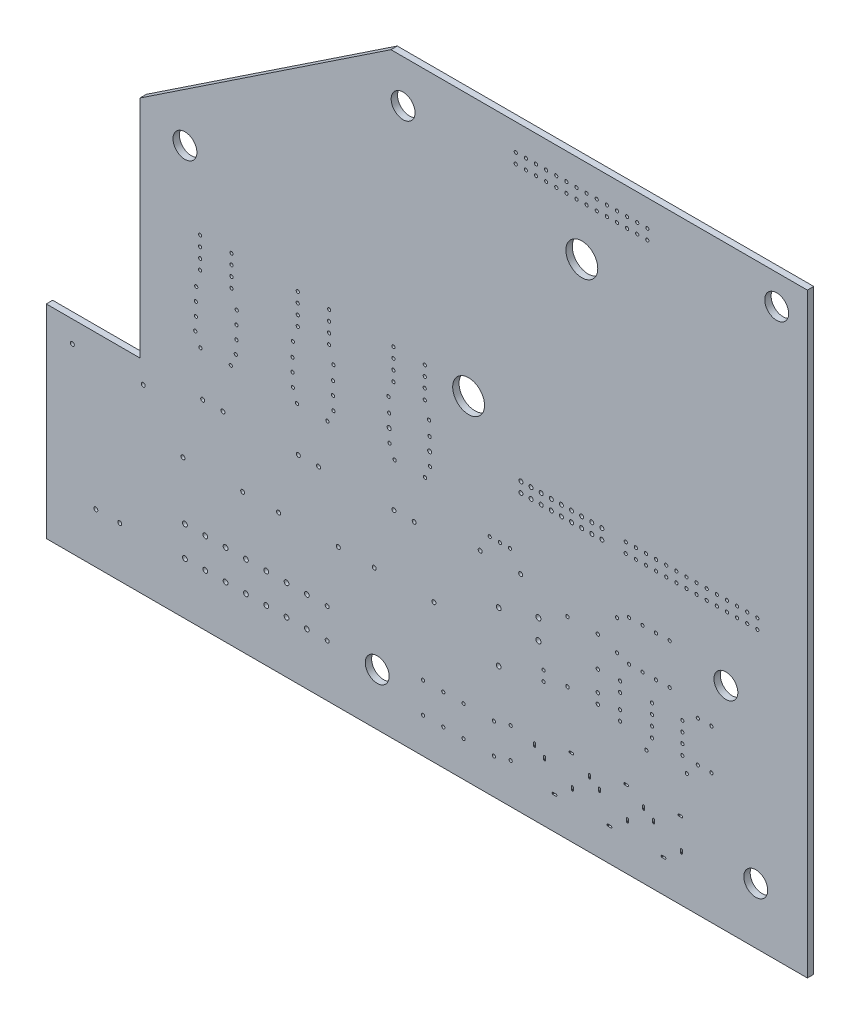
SolidWorks part; units mm, degrees
ref_plane "Front Plane" through (0, 0, 0) normal (0, 0, 1) x (1, 0, 0)
ref_plane "Top Plane" through (0, 0, 0) normal (0, 1, 0) x (1, 0, 0)
ref_plane "Right Plane" through (0, 0, 0) normal (1, 0, 0) x (0, 0, -1)
ref_plane "Plane1" through (0, 0, 0) normal (0, 0, -1) x (-1, 0, 0)
sketch "Sketch1" plane through (0, 0, 0) normal (0, 0, -1) x (-1, 0, 0)
  line L0 (-318, -203.5) -> (-127, -203.5)
  line L1 (-127, -203.5) -> (-127, -152.5)
  line L2 (-127, -152.5) -> (-150.5, -152.5)
  line L3 (-150.5, -152.5) -> (-150.5, -96)
  line L4 (-150.5, -96) -> (-213.5, -54)
  line L5 (-213.5, -54) -> (-318, -54)
  line L6 (-318, -54) -> (-318, -203.5)
  line L7 (-286.2232, -191.2732) -> (-286.169, -191.3543)
  line L8 (-286.169, -191.3543) -> (-286.15, -191.45)
  line L9 (-286.15, -191.45) -> (-286.15, -192.15)
  line L10 (-286.15, -192.15) -> (-286.169, -192.2457)
  line L11 (-286.169, -192.2457) -> (-286.2232, -192.3268)
  line L12 (-286.2232, -192.3268) -> (-286.3043, -192.381)
  line L13 (-286.3043, -192.381) -> (-286.4, -192.4)
  line L14 (-286.4, -192.4) -> (-286.4957, -192.381)
  line L15 (-286.4957, -192.381) -> (-286.5768, -192.3268)
  line L16 (-286.5768, -192.3268) -> (-286.631, -192.2457)
  line L17 (-286.631, -192.2457) -> (-286.65, -192.15)
  line L18 (-286.65, -192.15) -> (-286.65, -191.45)
  line L19 (-286.65, -191.45) -> (-286.631, -191.3543)
  line L20 (-286.631, -191.3543) -> (-286.5768, -191.2732)
  line L21 (-286.5768, -191.2732) -> (-286.4957, -191.219)
  line L22 (-286.4957, -191.219) -> (-286.4, -191.2)
  line L23 (-286.4, -191.2) -> (-286.3043, -191.219)
  line L24 (-286.3043, -191.219) -> (-286.2232, -191.2732)
  line L25 (-282.4268, -195.1232) -> (-282.3457, -195.069)
  line L26 (-282.3457, -195.069) -> (-282.25, -195.05)
  line L27 (-282.25, -195.05) -> (-281.55, -195.05)
  line L28 (-281.55, -195.05) -> (-281.4543, -195.069)
  line L29 (-281.4543, -195.069) -> (-281.3732, -195.1232)
  line L30 (-281.3732, -195.1232) -> (-281.319, -195.2043)
  line L31 (-281.319, -195.2043) -> (-281.3, -195.3)
  line L32 (-281.3, -195.3) -> (-281.319, -195.3957)
  line L33 (-281.319, -195.3957) -> (-281.3732, -195.4768)
  line L34 (-281.3732, -195.4768) -> (-281.4543, -195.531)
  line L35 (-281.4543, -195.531) -> (-281.55, -195.55)
  line L36 (-281.55, -195.55) -> (-282.25, -195.55)
  line L37 (-282.25, -195.55) -> (-282.3457, -195.531)
  line L38 (-282.3457, -195.531) -> (-282.4268, -195.4768)
  line L39 (-282.4268, -195.4768) -> (-282.481, -195.3957)
  line L40 (-282.481, -195.3957) -> (-282.5, -195.3)
  line L41 (-282.5, -195.3) -> (-282.481, -195.2043)
  line L42 (-282.481, -195.2043) -> (-282.4268, -195.1232)
  line L43 (-268.8718, -195.1232) -> (-268.7907, -195.069)
  line L44 (-268.7907, -195.069) -> (-268.695, -195.05)
  line L45 (-268.695, -195.05) -> (-267.995, -195.05)
  line L46 (-267.995, -195.05) -> (-267.8993, -195.069)
  line L47 (-267.8993, -195.069) -> (-267.8182, -195.1232)
  line L48 (-267.8182, -195.1232) -> (-267.764, -195.2043)
  line L49 (-267.764, -195.2043) -> (-267.745, -195.3)
  line L50 (-267.745, -195.3) -> (-267.764, -195.3957)
  line L51 (-267.764, -195.3957) -> (-267.8182, -195.4768)
  line L52 (-267.8182, -195.4768) -> (-267.8993, -195.531)
  line L53 (-267.8993, -195.531) -> (-267.995, -195.55)
  line L54 (-267.995, -195.55) -> (-268.695, -195.55)
  line L55 (-268.695, -195.55) -> (-268.7907, -195.531)
  line L56 (-268.7907, -195.531) -> (-268.8718, -195.4768)
  line L57 (-268.8718, -195.4768) -> (-268.926, -195.3957)
  line L58 (-268.926, -195.3957) -> (-268.945, -195.3)
  line L59 (-268.945, -195.3) -> (-268.926, -195.2043)
  line L60 (-268.926, -195.2043) -> (-268.8718, -195.1232)
  line L61 (-272.6682, -191.2732) -> (-272.614, -191.3543)
  line L62 (-272.614, -191.3543) -> (-272.595, -191.45)
  line L63 (-272.595, -191.45) -> (-272.595, -192.15)
  line L64 (-272.595, -192.15) -> (-272.614, -192.2457)
  line L65 (-272.614, -192.2457) -> (-272.6682, -192.3268)
  line L66 (-272.6682, -192.3268) -> (-272.7493, -192.381)
  line L67 (-272.7493, -192.381) -> (-272.845, -192.4)
  line L68 (-272.845, -192.4) -> (-272.9407, -192.381)
  line L69 (-272.9407, -192.381) -> (-273.0218, -192.3268)
  line L70 (-273.0218, -192.3268) -> (-273.076, -192.2457)
  line L71 (-273.076, -192.2457) -> (-273.095, -192.15)
  line L72 (-273.095, -192.15) -> (-273.095, -191.45)
  line L73 (-273.095, -191.45) -> (-273.076, -191.3543)
  line L74 (-273.076, -191.3543) -> (-273.0218, -191.2732)
  line L75 (-273.0218, -191.2732) -> (-272.9407, -191.219)
  line L76 (-272.9407, -191.219) -> (-272.845, -191.2)
  line L77 (-272.845, -191.2) -> (-272.7493, -191.219)
  line L78 (-272.7493, -191.219) -> (-272.6682, -191.2732)
  line L79 (-279.2232, -188.1732) -> (-279.169, -188.2543)
  line L80 (-279.169, -188.2543) -> (-279.15, -188.35)
  line L81 (-279.15, -188.35) -> (-279.15, -189.05)
  line L82 (-279.15, -189.05) -> (-279.169, -189.1457)
  line L83 (-279.169, -189.1457) -> (-279.2232, -189.2268)
  line L84 (-279.2232, -189.2268) -> (-279.3043, -189.281)
  line L85 (-279.3043, -189.281) -> (-279.4, -189.3)
  line L86 (-279.4, -189.3) -> (-279.4957, -189.281)
  line L87 (-279.4957, -189.281) -> (-279.5768, -189.2268)
  line L88 (-279.5768, -189.2268) -> (-279.631, -189.1457)
  line L89 (-279.631, -189.1457) -> (-279.65, -189.05)
  line L90 (-279.65, -189.05) -> (-279.65, -188.35)
  line L91 (-279.65, -188.35) -> (-279.631, -188.2543)
  line L92 (-279.631, -188.2543) -> (-279.5768, -188.1732)
  line L93 (-279.5768, -188.1732) -> (-279.4957, -188.119)
  line L94 (-279.4957, -188.119) -> (-279.4, -188.1)
  line L95 (-279.4, -188.1) -> (-279.3043, -188.119)
  line L96 (-279.3043, -188.119) -> (-279.2232, -188.1732)
  line L97 (-276.7232, -186.4732) -> (-276.669, -186.5543)
  line L98 (-276.669, -186.5543) -> (-276.65, -186.65)
  line L99 (-276.65, -186.65) -> (-276.65, -187.35)
  line L100 (-276.65, -187.35) -> (-276.669, -187.4457)
  line L101 (-276.669, -187.4457) -> (-276.7232, -187.5268)
  line L102 (-276.7232, -187.5268) -> (-276.8043, -187.581)
  line L103 (-276.8043, -187.581) -> (-276.9, -187.6)
  line L104 (-276.9, -187.6) -> (-276.9957, -187.581)
  line L105 (-276.9957, -187.581) -> (-277.0768, -187.5268)
  line L106 (-277.0768, -187.5268) -> (-277.131, -187.4457)
  line L107 (-277.131, -187.4457) -> (-277.15, -187.35)
  line L108 (-277.15, -187.35) -> (-277.15, -186.65)
  line L109 (-277.15, -186.65) -> (-277.131, -186.5543)
  line L110 (-277.131, -186.5543) -> (-277.0768, -186.4732)
  line L111 (-277.0768, -186.4732) -> (-276.9957, -186.419)
  line L112 (-276.9957, -186.419) -> (-276.9, -186.4)
  line L113 (-276.9, -186.4) -> (-276.8043, -186.419)
  line L114 (-276.8043, -186.419) -> (-276.7232, -186.4732)
  line L115 (-286.6268, -184.0232) -> (-286.5457, -183.969)
  line L116 (-286.5457, -183.969) -> (-286.45, -183.95)
  line L117 (-286.45, -183.95) -> (-285.75, -183.95)
  line L118 (-285.75, -183.95) -> (-285.6543, -183.969)
  line L119 (-285.6543, -183.969) -> (-285.5732, -184.0232)
  line L120 (-285.5732, -184.0232) -> (-285.519, -184.1043)
  line L121 (-285.519, -184.1043) -> (-285.5, -184.2)
  line L122 (-285.5, -184.2) -> (-285.519, -184.2957)
  line L123 (-285.519, -184.2957) -> (-285.5732, -184.3768)
  line L124 (-285.5732, -184.3768) -> (-285.6543, -184.431)
  line L125 (-285.6543, -184.431) -> (-285.75, -184.45)
  line L126 (-285.75, -184.45) -> (-286.45, -184.45)
  line L127 (-286.45, -184.45) -> (-286.5457, -184.431)
  line L128 (-286.5457, -184.431) -> (-286.6268, -184.3768)
  line L129 (-286.6268, -184.3768) -> (-286.681, -184.2957)
  line L130 (-286.681, -184.2957) -> (-286.7, -184.2)
  line L131 (-286.7, -184.2) -> (-286.681, -184.1043)
  line L132 (-286.681, -184.1043) -> (-286.6268, -184.0232)
  line L133 (-273.0718, -184.0232) -> (-272.9907, -183.969)
  line L134 (-272.9907, -183.969) -> (-272.895, -183.95)
  line L135 (-272.895, -183.95) -> (-272.195, -183.95)
  line L136 (-272.195, -183.95) -> (-272.0993, -183.969)
  line L137 (-272.0993, -183.969) -> (-272.0182, -184.0232)
  line L138 (-272.0182, -184.0232) -> (-271.964, -184.1043)
  line L139 (-271.964, -184.1043) -> (-271.945, -184.2)
  line L140 (-271.945, -184.2) -> (-271.964, -184.2957)
  line L141 (-271.964, -184.2957) -> (-272.0182, -184.3768)
  line L142 (-272.0182, -184.3768) -> (-272.0993, -184.431)
  line L143 (-272.0993, -184.431) -> (-272.195, -184.45)
  line L144 (-272.195, -184.45) -> (-272.895, -184.45)
  line L145 (-272.895, -184.45) -> (-272.9907, -184.431)
  line L146 (-272.9907, -184.431) -> (-273.0718, -184.3768)
  line L147 (-273.0718, -184.3768) -> (-273.126, -184.2957)
  line L148 (-273.126, -184.2957) -> (-273.145, -184.2)
  line L149 (-273.145, -184.2) -> (-273.126, -184.1043)
  line L150 (-273.126, -184.1043) -> (-273.0718, -184.0232)
  line L151 (-258.8682, -191.2732) -> (-258.814, -191.3543)
  line L152 (-258.814, -191.3543) -> (-258.795, -191.45)
  line L153 (-258.795, -191.45) -> (-258.795, -192.15)
  line L154 (-258.795, -192.15) -> (-258.814, -192.2457)
  line L155 (-258.814, -192.2457) -> (-258.8682, -192.3268)
  line L156 (-258.8682, -192.3268) -> (-258.9493, -192.381)
  line L157 (-258.9493, -192.381) -> (-259.045, -192.4)
  line L158 (-259.045, -192.4) -> (-259.1407, -192.381)
  line L159 (-259.1407, -192.381) -> (-259.2218, -192.3268)
  line L160 (-259.2218, -192.3268) -> (-259.276, -192.2457)
  line L161 (-259.276, -192.2457) -> (-259.295, -192.15)
  line L162 (-259.295, -192.15) -> (-259.295, -191.45)
  line L163 (-259.295, -191.45) -> (-259.276, -191.3543)
  line L164 (-259.276, -191.3543) -> (-259.2218, -191.2732)
  line L165 (-259.2218, -191.2732) -> (-259.1407, -191.219)
  line L166 (-259.1407, -191.219) -> (-259.045, -191.2)
  line L167 (-259.045, -191.2) -> (-258.9493, -191.219)
  line L168 (-258.9493, -191.219) -> (-258.8682, -191.2732)
  line L169 (-265.6682, -188.1732) -> (-265.614, -188.2543)
  line L170 (-265.614, -188.2543) -> (-265.595, -188.35)
  line L171 (-265.595, -188.35) -> (-265.595, -189.05)
  line L172 (-265.595, -189.05) -> (-265.614, -189.1457)
  line L173 (-265.614, -189.1457) -> (-265.6682, -189.2268)
  line L174 (-265.6682, -189.2268) -> (-265.7493, -189.281)
  line L175 (-265.7493, -189.281) -> (-265.845, -189.3)
  line L176 (-265.845, -189.3) -> (-265.9407, -189.281)
  line L177 (-265.9407, -189.281) -> (-266.0218, -189.2268)
  line L178 (-266.0218, -189.2268) -> (-266.076, -189.1457)
  line L179 (-266.076, -189.1457) -> (-266.095, -189.05)
  line L180 (-266.095, -189.05) -> (-266.095, -188.35)
  line L181 (-266.095, -188.35) -> (-266.076, -188.2543)
  line L182 (-266.076, -188.2543) -> (-266.0218, -188.1732)
  line L183 (-266.0218, -188.1732) -> (-265.9407, -188.119)
  line L184 (-265.9407, -188.119) -> (-265.845, -188.1)
  line L185 (-265.845, -188.1) -> (-265.7493, -188.119)
  line L186 (-265.7493, -188.119) -> (-265.6682, -188.1732)
  line L187 (-263.1682, -186.4732) -> (-263.114, -186.5543)
  line L188 (-263.114, -186.5543) -> (-263.095, -186.65)
  line L189 (-263.095, -186.65) -> (-263.095, -187.35)
  line L190 (-263.095, -187.35) -> (-263.114, -187.4457)
  line L191 (-263.114, -187.4457) -> (-263.1682, -187.5268)
  line L192 (-263.1682, -187.5268) -> (-263.2493, -187.581)
  line L193 (-263.2493, -187.581) -> (-263.345, -187.6)
  line L194 (-263.345, -187.6) -> (-263.4407, -187.581)
  line L195 (-263.4407, -187.581) -> (-263.5218, -187.5268)
  line L196 (-263.5218, -187.5268) -> (-263.576, -187.4457)
  line L197 (-263.576, -187.4457) -> (-263.595, -187.35)
  line L198 (-263.595, -187.35) -> (-263.595, -186.65)
  line L199 (-263.595, -186.65) -> (-263.576, -186.5543)
  line L200 (-263.576, -186.5543) -> (-263.5218, -186.4732)
  line L201 (-263.5218, -186.4732) -> (-263.4407, -186.419)
  line L202 (-263.4407, -186.419) -> (-263.345, -186.4)
  line L203 (-263.345, -186.4) -> (-263.2493, -186.419)
  line L204 (-263.2493, -186.419) -> (-263.1682, -186.4732)
  line L205 (-255.0718, -195.1232) -> (-254.9907, -195.069)
  line L206 (-254.9907, -195.069) -> (-254.895, -195.05)
  line L207 (-254.895, -195.05) -> (-254.195, -195.05)
  line L208 (-254.195, -195.05) -> (-254.0993, -195.069)
  line L209 (-254.0993, -195.069) -> (-254.0182, -195.1232)
  line L210 (-254.0182, -195.1232) -> (-253.964, -195.2043)
  line L211 (-253.964, -195.2043) -> (-253.945, -195.3)
  line L212 (-253.945, -195.3) -> (-253.964, -195.3957)
  line L213 (-253.964, -195.3957) -> (-254.0182, -195.4768)
  line L214 (-254.0182, -195.4768) -> (-254.0993, -195.531)
  line L215 (-254.0993, -195.531) -> (-254.195, -195.55)
  line L216 (-254.195, -195.55) -> (-254.895, -195.55)
  line L217 (-254.895, -195.55) -> (-254.9907, -195.531)
  line L218 (-254.9907, -195.531) -> (-255.0718, -195.4768)
  line L219 (-255.0718, -195.4768) -> (-255.126, -195.3957)
  line L220 (-255.126, -195.3957) -> (-255.145, -195.3)
  line L221 (-255.145, -195.3) -> (-255.126, -195.2043)
  line L222 (-255.126, -195.2043) -> (-255.0718, -195.1232)
  line L223 (-251.8682, -188.1732) -> (-251.814, -188.2543)
  line L224 (-251.814, -188.2543) -> (-251.795, -188.35)
  line L225 (-251.795, -188.35) -> (-251.795, -189.05)
  line L226 (-251.795, -189.05) -> (-251.814, -189.1457)
  line L227 (-251.814, -189.1457) -> (-251.8682, -189.2268)
  line L228 (-251.8682, -189.2268) -> (-251.9493, -189.281)
  line L229 (-251.9493, -189.281) -> (-252.045, -189.3)
  line L230 (-252.045, -189.3) -> (-252.1407, -189.281)
  line L231 (-252.1407, -189.281) -> (-252.2218, -189.2268)
  line L232 (-252.2218, -189.2268) -> (-252.276, -189.1457)
  line L233 (-252.276, -189.1457) -> (-252.295, -189.05)
  line L234 (-252.295, -189.05) -> (-252.295, -188.35)
  line L235 (-252.295, -188.35) -> (-252.276, -188.2543)
  line L236 (-252.276, -188.2543) -> (-252.2218, -188.1732)
  line L237 (-252.2218, -188.1732) -> (-252.1407, -188.119)
  line L238 (-252.1407, -188.119) -> (-252.045, -188.1)
  line L239 (-252.045, -188.1) -> (-251.9493, -188.119)
  line L240 (-251.9493, -188.119) -> (-251.8682, -188.1732)
  line L241 (-249.3682, -186.4732) -> (-249.314, -186.5543)
  line L242 (-249.314, -186.5543) -> (-249.295, -186.65)
  line L243 (-249.295, -186.65) -> (-249.295, -187.35)
  line L244 (-249.295, -187.35) -> (-249.314, -187.4457)
  line L245 (-249.314, -187.4457) -> (-249.3682, -187.5268)
  line L246 (-249.3682, -187.5268) -> (-249.4493, -187.581)
  line L247 (-249.4493, -187.581) -> (-249.545, -187.6)
  line L248 (-249.545, -187.6) -> (-249.6407, -187.581)
  line L249 (-249.6407, -187.581) -> (-249.7218, -187.5268)
  line L250 (-249.7218, -187.5268) -> (-249.776, -187.4457)
  line L251 (-249.776, -187.4457) -> (-249.795, -187.35)
  line L252 (-249.795, -187.35) -> (-249.795, -186.65)
  line L253 (-249.795, -186.65) -> (-249.776, -186.5543)
  line L254 (-249.776, -186.5543) -> (-249.7218, -186.4732)
  line L255 (-249.7218, -186.4732) -> (-249.6407, -186.419)
  line L256 (-249.6407, -186.419) -> (-249.545, -186.4)
  line L257 (-249.545, -186.4) -> (-249.4493, -186.419)
  line L258 (-249.4493, -186.419) -> (-249.3682, -186.4732)
  line L259 (-259.2718, -184.0232) -> (-259.1907, -183.969)
  line L260 (-259.1907, -183.969) -> (-259.095, -183.95)
  line L261 (-259.095, -183.95) -> (-258.395, -183.95)
  line L262 (-258.395, -183.95) -> (-258.2993, -183.969)
  line L263 (-258.2993, -183.969) -> (-258.2182, -184.0232)
  line L264 (-258.2182, -184.0232) -> (-258.164, -184.1043)
  line L265 (-258.164, -184.1043) -> (-258.145, -184.2)
  line L266 (-258.145, -184.2) -> (-258.164, -184.2957)
  line L267 (-258.164, -184.2957) -> (-258.2182, -184.3768)
  line L268 (-258.2182, -184.3768) -> (-258.2993, -184.431)
  line L269 (-258.2993, -184.431) -> (-258.395, -184.45)
  line L270 (-258.395, -184.45) -> (-259.095, -184.45)
  line L271 (-259.095, -184.45) -> (-259.1907, -184.431)
  line L272 (-259.1907, -184.431) -> (-259.2718, -184.3768)
  line L273 (-259.2718, -184.3768) -> (-259.326, -184.2957)
  line L274 (-259.326, -184.2957) -> (-259.345, -184.2)
  line L275 (-259.345, -184.2) -> (-259.326, -184.1043)
  line L276 (-259.326, -184.1043) -> (-259.2718, -184.0232)
  circle A0 centre (-305.05, -189.44) radius 3
  circle A1 centre (-293.91, -170.95) radius 0.4
  circle A2 centre (-287.755, -174.19) radius 0.4
  circle A3 centre (-290.51, -170.95) radius 0.4
  circle A4 centre (-286.625, -170.81) radius 0.4
  circle A5 centre (-277.595, -174.19) radius 0.4
  circle A6 centre (-279.005, -170.81) radius 0.4
  circle A7 centre (-271.005, -171.19) radius 0.4
  circle A8 centre (-286.625, -168.27) radius 0.4
  circle A9 centre (-286.625, -165.73) radius 0.4
  circle A10 centre (-286.625, -163.19) radius 0.4
  circle A11 centre (-279.005, -168.27) radius 0.4
  circle A12 centre (-279.005, -165.73) radius 0.4
  circle A13 centre (-271.005, -168.69) radius 0.4
  circle A14 centre (-279.005, -163.19) radius 0.4
  circle A15 centre (-271.005, -164.94) radius 0.4
  circle A16 centre (-271.005, -162.44) radius 0.4
  circle A17 centre (-243.55, -193.44) radius 0.4
  circle A18 centre (-239.34, -194.62) radius 0.4
  circle A19 centre (-239.34, -187) radius 0.4
  circle A20 centre (-231.72, -194.62) radius 0.4
  circle A21 centre (-226.64, -194.62) radius 0.4
  circle A22 centre (-231.72, -187) radius 0.4
  circle A23 centre (-226.64, -187) radius 0.4
  circle A24 centre (-243.55, -185.82) radius 0.4
  circle A25 centre (-265.42, -170.31) radius 0.425
  circle A26 centre (-257.8, -170.31) radius 0.425
  circle A27 centre (-251.8, -172.19) radius 0.4
  circle A28 centre (-265.42, -167.77) radius 0.425
  circle A29 centre (-265.42, -162.69) radius 0.425
  circle A30 centre (-251.8, -169.69) radius 0.4
  circle A31 centre (-250.5, -163.94) radius 0.65
  circle A32 centre (-240.55, -174.44) radius 0.6
  circle A33 centre (-240.55, -161.74) radius 0.6
  circle A34 centre (-224.293, -168.683) radius 0.5
  circle A35 centre (-293.91, -160.79) radius 0.4
  circle A36 centre (-297.55, -150.19) radius 3
  circle A37 centre (-290.51, -160.79) radius 0.4
  circle A38 centre (-283.45, -157.635) radius 0.4
  circle A39 centre (-280.005, -157.69) radius 0.4
  circle A40 centre (-276.64, -157.69) radius 0.4
  circle A41 centre (-273.255, -157.69) radius 0.4
  circle A42 centre (-270.255, -156.69) radius 0.4
  circle A43 centre (-283.45, -147.475) radius 0.4
  circle A44 centre (-280.005, -147.53) radius 0.4
  circle A45 centre (-270.255, -149.07) radius 0.4
  circle A46 centre (-276.64, -147.53) radius 0.4
  circle A47 centre (-273.255, -147.53) radius 0.4
  circle A48 centre (-305.44, -134.04) radius 0.4
  circle A49 centre (-302.9, -134.04) radius 0.4
  circle A50 centre (-305.44, -131.5) radius 0.4
  circle A51 centre (-302.9, -131.5) radius 0.4
  circle A52 centre (-300.36, -134.04) radius 0.4
  circle A53 centre (-297.82, -134.04) radius 0.4
  circle A54 centre (-300.36, -131.5) radius 0.4
  circle A55 centre (-297.82, -131.5) radius 0.4
  circle A56 centre (-295.28, -134.04) radius 0.4
  circle A57 centre (-292.74, -134.04) radius 0.4
  circle A58 centre (-295.28, -131.5) radius 0.4
  circle A59 centre (-292.74, -131.5) radius 0.4
  circle A60 centre (-290.2, -134.04) radius 0.4
  circle A61 centre (-287.66, -134.04) radius 0.4
  circle A62 centre (-290.2, -131.5) radius 0.4
  circle A63 centre (-287.66, -131.5) radius 0.4
  circle A64 centre (-285.12, -134.04) radius 0.4
  circle A65 centre (-282.58, -134.04) radius 0.4
  circle A66 centre (-280.04, -134.04) radius 0.4
  circle A67 centre (-285.12, -131.5) radius 0.4
  circle A68 centre (-282.58, -131.5) radius 0.4
  circle A69 centre (-280.04, -131.5) radius 0.4
  circle A70 centre (-277.5, -134.04) radius 0.4
  circle A71 centre (-274.96, -134.04) radius 0.4
  circle A72 centre (-277.5, -131.5) radius 0.4
  circle A73 centre (-274.96, -131.5) radius 0.4
  circle A74 centre (-272.42, -134.04) radius 0.4
  circle A75 centre (-272.42, -131.5) radius 0.4
  circle A76 centre (-265.42, -155.07) radius 0.425
  circle A77 centre (-257.8, -155.07) radius 0.425
  circle A78 centre (-250.5, -158.94) radius 0.65
  circle A79 centre (-246.05, -151.69) radius 0.5
  circle A80 centre (-235.89, -151.69) radius 0.5
  circle A81 centre (-243.38, -147.44) radius 0.4
  circle A82 centre (-240.84, -147.44) radius 0.4
  circle A83 centre (-238.3, -147.44) radius 0.4
  circle A84 centre (-266.44, -134.04) radius 0.5
  circle A85 centre (-263.9, -134.04) radius 0.5
  circle A86 centre (-266.44, -131.5) radius 0.5
  circle A87 centre (-263.9, -131.5) radius 0.5
  circle A88 centre (-261.36, -134.04) radius 0.5
  circle A89 centre (-258.82, -134.04) radius 0.5
  circle A90 centre (-261.36, -131.5) radius 0.5
  circle A91 centre (-258.82, -131.5) radius 0.5
  circle A92 centre (-256.28, -134.04) radius 0.5
  circle A93 centre (-253.74, -134.04) radius 0.5
  circle A94 centre (-256.28, -131.5) radius 0.5
  circle A95 centre (-253.74, -131.5) radius 0.5
  circle A96 centre (-251.2, -134.04) radius 0.5
  circle A97 centre (-248.66, -134.04) radius 0.5
  circle A98 centre (-246.12, -134.04) radius 0.5
  circle A99 centre (-251.2, -131.5) radius 0.5
  circle A100 centre (-248.66, -131.5) radius 0.5
  circle A101 centre (-246.12, -131.5) radius 0.5
  circle A102 centre (-223.3, -139.69) radius 0.4
  circle A103 centre (-223.21, -136.44) radius 0.5
  circle A104 centre (-223.21, -133.19) radius 0.4
  circle A105 centre (-221.56, -194.62) radius 0.4
  circle A106 centre (-221.56, -187) radius 0.4
  circle A107 centre (-210.05, -190.44) radius 3
  circle A108 centre (-197.5, -190.44) radius 0.5
  circle A109 centre (-192.4, -190.44) radius 0.6
  circle A110 centre (-187.3, -190.44) radius 0.6
  circle A111 centre (-182.2, -190.44) radius 0.6
  circle A112 centre (-197.5, -182.94) radius 0.5
  circle A113 centre (-192.4, -182.94) radius 0.6
  circle A114 centre (-187.3, -182.94) radius 0.6
  circle A115 centre (-182.2, -182.94) radius 0.6
  circle A116 centre (-209.307, -168.683) radius 0.5
  circle A117 centre (-200.293, -168.683) radius 0.5
  circle A118 centre (-185.307, -168.683) radius 0.5
  circle A119 centre (-177.1, -190.44) radius 0.6
  circle A120 centre (-172, -190.44) radius 0.6
  circle A121 centre (-166.9, -190.44) radius 0.6
  circle A122 centre (-161.8, -190.44) radius 0.6
  circle A123 centre (-177.1, -182.94) radius 0.6
  circle A124 centre (-172, -182.94) radius 0.6
  circle A125 centre (-166.9, -182.94) radius 0.6
  circle A126 centre (-161.8, -182.94) radius 0.6
  circle A127 centre (-145.44, -190.91) radius 0.5
  circle A128 centre (-139.44, -190.91) radius 0.5
  circle A129 centre (-176.293, -168.683) radius 0.5
  circle A130 centre (-161.307, -168.683) radius 0.5
  circle A131 centre (-219.34, -153.697) radius 0.5
  circle A132 centre (-214.26, -153.697) radius 0.5
  circle A133 centre (-195.34, -153.697) radius 0.5
  circle A134 centre (-190.26, -153.697) radius 0.5
  circle A135 centre (-222.05, -142.69) radius 0.4
  circle A136 centre (-214.43, -142.69) radius 0.4
  circle A137 centre (-213.14, -139.69) radius 0.4
  circle A138 centre (-213.05, -136.44) radius 0.5
  circle A139 centre (-213.05, -133.19) radius 0.4
  circle A140 centre (-223.05, -129.69) radius 0.4
  circle A141 centre (-212.89, -129.69) radius 0.4
  circle A142 centre (-197.55, -142.69) radius 0.4
  circle A143 centre (-189.93, -142.69) radius 0.4
  circle A144 centre (-199.05, -139.69) radius 0.4
  circle A145 centre (-198.96, -136.44) radius 0.4
  circle A146 centre (-188.89, -139.69) radius 0.4
  circle A147 centre (-188.8, -136.44) radius 0.4
  circle A148 centre (-198.96, -133.19) radius 0.4
  circle A149 centre (-199.05, -129.69) radius 0.4
  circle A150 centre (-188.8, -133.19) radius 0.4
  circle A151 centre (-188.89, -129.69) radius 0.4
  circle A152 centre (-171.34, -153.697) radius 0.5
  circle A153 centre (-166.26, -153.697) radius 0.5
  circle A154 centre (-151.34, -157.91) radius 0.5
  circle A155 centre (-133.54, -157.91) radius 0.5
  circle A156 centre (-173.3, -142.69) radius 0.4
  circle A157 centre (-174.55, -139.69) radius 0.4
  circle A158 centre (-174.71, -136.44) radius 0.4
  circle A159 centre (-165.68, -142.69) radius 0.4
  circle A160 centre (-164.39, -139.69) radius 0.4
  circle A161 centre (-164.55, -136.44) radius 0.4
  circle A162 centre (-174.71, -133.19) radius 0.4
  circle A163 centre (-174.8, -129.94) radius 0.4
  circle A164 centre (-164.55, -133.19) radius 0.4
  circle A165 centre (-164.64, -129.94) radius 0.4
  circle A166 centre (-232.99, -119.55) radius 4
  circle A167 centre (-310.3, -61.44) radius 3
  circle A168 centre (-277.84, -63.2) radius 0.4
  circle A169 centre (-275.3, -63.2) radius 0.4
  circle A170 centre (-272.76, -63.2) radius 0.4
  circle A171 centre (-270.22, -63.2) radius 0.4
  circle A172 centre (-277.84, -60.66) radius 0.4
  circle A173 centre (-275.3, -60.66) radius 0.4
  circle A174 centre (-272.76, -60.66) radius 0.4
  circle A175 centre (-270.22, -60.66) radius 0.4
  circle A176 centre (-261.4, -75.61) radius 4
  circle A177 centre (-267.68, -63.2) radius 0.4
  circle A178 centre (-265.14, -63.2) radius 0.4
  circle A179 centre (-262.6, -63.2) radius 0.4
  circle A180 centre (-260.06, -63.2) radius 0.4
  circle A181 centre (-257.52, -63.2) radius 0.4
  circle A182 centre (-267.68, -60.66) radius 0.4
  circle A183 centre (-265.14, -60.66) radius 0.4
  circle A184 centre (-262.6, -60.66) radius 0.4
  circle A185 centre (-260.06, -60.66) radius 0.4
  circle A186 centre (-257.52, -60.66) radius 0.4
  circle A187 centre (-254.98, -63.2) radius 0.4
  circle A188 centre (-252.44, -63.2) radius 0.4
  circle A189 centre (-249.9, -63.2) radius 0.4
  circle A190 centre (-247.36, -63.2) radius 0.4
  circle A191 centre (-254.98, -60.66) radius 0.4
  circle A192 centre (-252.44, -60.66) radius 0.4
  circle A193 centre (-249.9, -60.66) radius 0.4
  circle A194 centre (-247.36, -60.66) radius 0.4
  circle A195 centre (-244.82, -63.2) radius 0.4
  circle A196 centre (-244.82, -60.66) radius 0.4
  circle A197 centre (-221.985, -125.86) radius 0.4
  circle A198 centre (-221.985, -123.32) radius 0.4
  circle A199 centre (-214.115, -125.86) radius 0.4
  circle A200 centre (-214.115, -123.32) radius 0.4
  circle A201 centre (-221.985, -120.78) radius 0.4
  circle A202 centre (-214.115, -120.78) radius 0.4
  circle A203 centre (-221.985, -118.24) radius 0.4
  circle A204 centre (-214.115, -118.24) radius 0.4
  circle A205 centre (-197.985, -125.86) radius 0.4
  circle A206 centre (-197.985, -123.32) radius 0.4
  circle A207 centre (-190.115, -125.86) radius 0.4
  circle A208 centre (-190.115, -123.32) radius 0.4
  circle A209 centre (-197.985, -120.78) radius 0.4
  circle A210 centre (-190.115, -120.78) radius 0.4
  circle A211 centre (-197.985, -118.24) radius 0.4
  circle A212 centre (-190.115, -118.24) radius 0.4
  circle A213 centre (-173.485, -125.86) radius 0.4
  circle A214 centre (-173.485, -123.32) radius 0.4
  circle A215 centre (-173.485, -120.78) radius 0.4
  circle A216 centre (-165.615, -125.86) radius 0.4
  circle A217 centre (-165.615, -123.32) radius 0.4
  circle A218 centre (-165.615, -120.78) radius 0.4
  circle A219 centre (-173.485, -118.24) radius 0.4
  circle A220 centre (-165.615, -118.24) radius 0.4
  circle A221 centre (-161.8, -100.69) radius 3
  circle A222 centre (-216.55, -64.69) radius 3
extrude "Boss-Extrude1" add sketch "Sketch1" against normal blind 1.6
